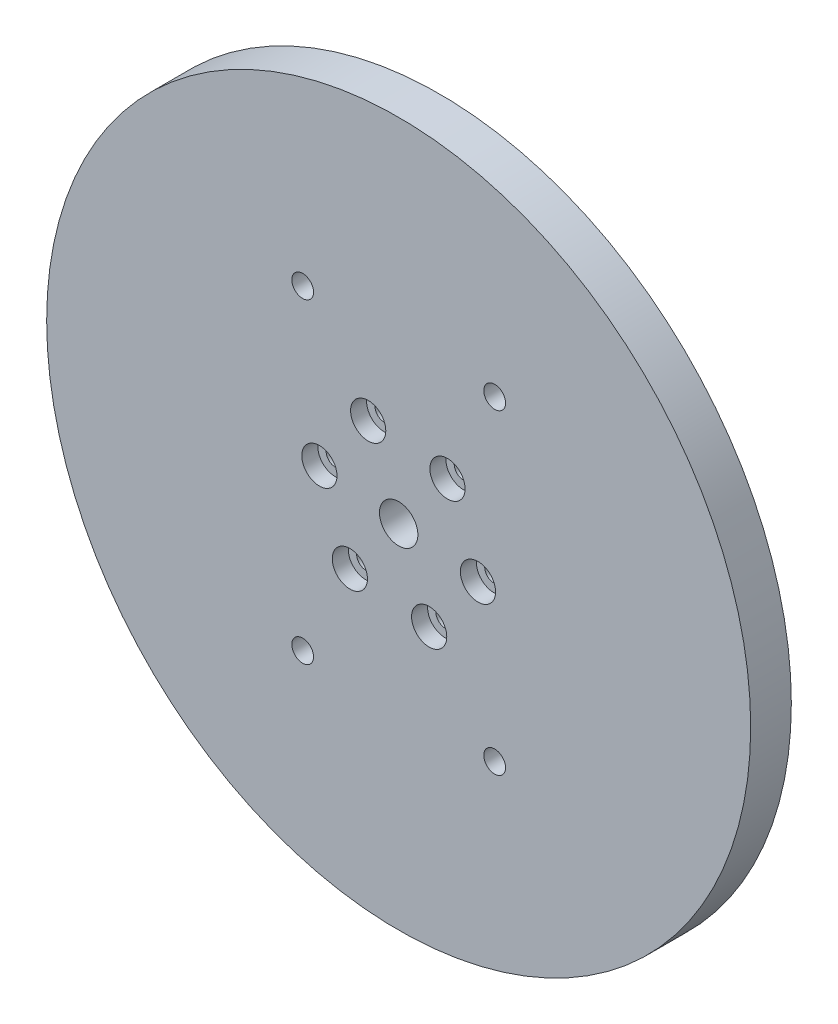
SolidWorks part; units mm, degrees
material "Aleación 6061"
ref_plane "Alzado" through (0, 0, 0) normal (0, 0, 1) x (1, 0, 0)
ref_plane "Planta" through (0, 0, 0) normal (0, 1, 0) x (1, 0, 0)
ref_plane "Vista lateral" through (0, 0, 0) normal (1, 0, 0) x (0, 0, -1)
sketch "Sk_Disco" plane through (0, 0, 0) normal (0, 0, 1) x (1, 0, 0)
  circle A0 centre (0, 0) radius 55
  dimension "D1" = 110
extrude "Disco" add sketch "Sk_Disco" along normal blind 6.35 from offset 420
sketch "Sk_Pasantes_M2-5_rotor_J4" plane through (0, 0, 0) normal (0, 0, 1) x (1, 0, 0)
  circle A0 centre (12.3902, -1.6532) radius 1.45
  circle A1 centre (7.6268, 9.9036) radius 1.45
  circle A2 centre (-4.7634, 11.5568) radius 1.45
  circle A3 centre (-12.3902, 1.6532) radius 1.45
  circle A4 centre (-7.6268, -9.9036) radius 1.45
  circle A5 centre (4.7634, -11.5568) radius 1.45
  dimension "D1" = 2.9
  dimension "D4" = 2.9
  dimension "D7" = 2.9
  dimension "D10" = 2.9
  dimension "D13" = 2.9
  dimension "D16" = 2.9
  dimension "D2" = 12.3902
  dimension "D3" = 1.6532
  dimension "D5" = 7.6268
  dimension "D6" = 9.9036
  dimension "D8" = 4.7634
  dimension "D9" = 11.5568
  dimension "D11" = 12.3902
  dimension "D12" = 1.6532
  dimension "D14" = 7.6268
  dimension "D15" = 9.9036
  dimension "D17" = 4.7634
  dimension "D18" = 11.5568
extrude "Pasantes_M2-5_rotor_J4" cut sketch "Sk_Pasantes_M2-5_rotor_J4" along normal blind 6.35 from offset 420
sketch "Sk_Cajas_M2-5" plane through (0, 0, 0) normal (0, 0, 1) x (1, 0, 0)
  circle A0 centre (12.3902, -1.6532) radius 2.75
  circle A1 centre (7.6268, 9.9036) radius 2.75
  circle A2 centre (-4.7634, 11.5568) radius 2.75
  circle A3 centre (-12.3902, 1.6532) radius 2.75
  circle A4 centre (-7.6268, -9.9036) radius 2.75
  circle A5 centre (4.7634, -11.5568) radius 2.75
  dimension "D1" = 5.5
  dimension "D4" = 5.5
  dimension "D7" = 5.5
  dimension "D10" = 5.5
  dimension "D13" = 5.5
  dimension "D16" = 5.5
  dimension "D2" = 12.3902
  dimension "D3" = 1.6532
  dimension "D5" = 7.6268
  dimension "D6" = 9.9036
  dimension "D8" = 4.7634
  dimension "D9" = 11.5568
  dimension "D11" = 12.3902
  dimension "D12" = 1.6532
  dimension "D14" = 7.6268
  dimension "D15" = 9.9036
  dimension "D17" = 4.7634
  dimension "D18" = 11.5568
extrude "Cajas_M2-5" cut sketch "Sk_Cajas_M2-5" along normal blind 2.5 from offset 423.85
sketch "Sk_Paso_cable" plane through (0, 0, 0) normal (0, 0, 1) x (1, 0, 0)
  circle A0 centre (0, 0) radius 3
  dimension "D1" = 6
extrude "Paso_cable" cut sketch "Sk_Paso_cable" along normal blind 6.35 from offset 420
sketch "Sk_Pasantes_M4_angulos" plane through (0, 0, 0) normal (0, 0, 1) x (1, 0, 0)
  circle A0 centre (-10, -38.61) radius 2.25
  circle A1 centre (-10, 38.61) radius 2.25
  circle A2 centre (10, -38.61) radius 2.25
  circle A3 centre (10, 38.61) radius 2.25
  dimension "D1" = 4.5
  dimension "D4" = 4.5
  dimension "D7" = 4.5
  dimension "D10" = 4.5
  dimension "D2" = 10
  dimension "D3" = 38.61
  dimension "D5" = 10
  dimension "D6" = 38.61
  dimension "D8" = 10
  dimension "D9" = 38.61
  dimension "D11" = 10
  dimension "D12" = 38.61
sketch "Sk_Rosca_M4_angulos_interiores" plane through (0, 0, 426.35) normal (0, 0, 1) x (1, 0, 0)
  circle A0 centre (-20, -10.39) radius 1.65
  circle A1 centre (-20, 10.39) radius 1.65
  circle A2 centre (20, -10.39) radius 1.65
  circle A3 centre (20, 10.39) radius 1.65
sketch "Sk_Pasantes_M3_paredes" plane through (0, 0, 426.35) normal (0, 0, 1) x (1, 0, 0)
  circle A0 centre (-15, -24.675) radius 1.7
  circle A1 centre (15, -24.675) radius 1.7
  circle A2 centre (-15, 24.675) radius 1.7
  circle A3 centre (15, 24.675) radius 1.7
extrude "Pasantes_M3_paredes" cut sketch "Sk_Pasantes_M3_paredes" against normal through all
sketch "Sk_Cajas_M3_paredes" plane through (0, 0, 420) normal (0, 0, -1) x (-1, 0, 0)
  circle A0 centre (15, -24.675) radius 3.25
  circle A1 centre (-15, -24.675) radius 3.25
  circle A2 centre (15, 24.675) radius 3.25
  circle A3 centre (-15, 24.675) radius 3.25
extrude "Cajas_M3_paredes" cut sketch "Sk_Cajas_M3_paredes" against normal blind 3.5
